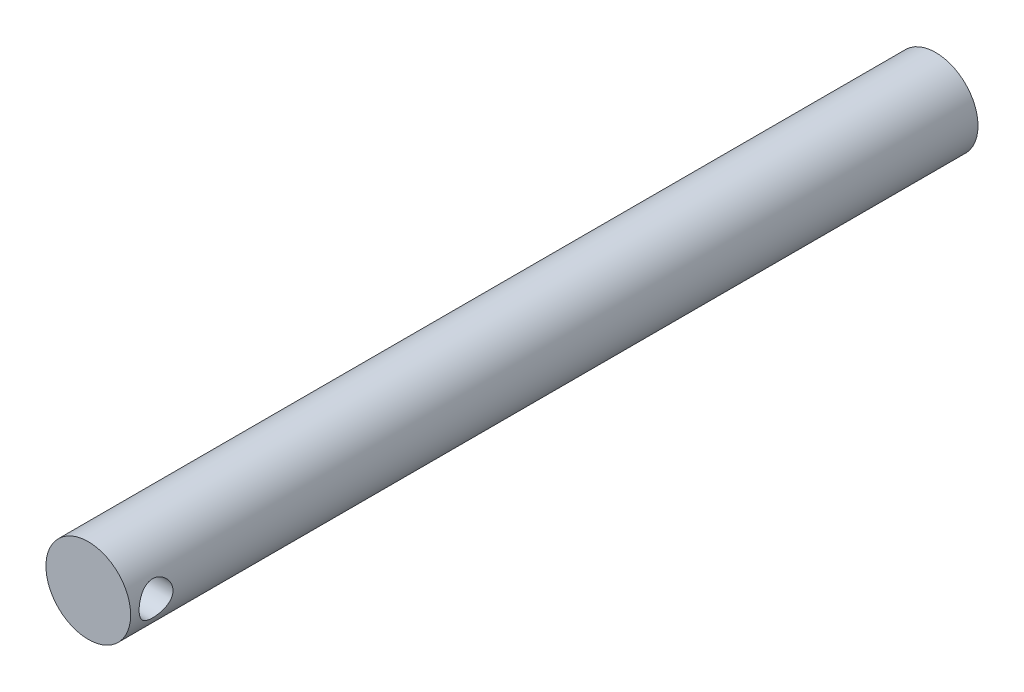
SolidWorks part; units mm, degrees
ref_plane "前视基准面" through (0, 0, 0) normal (0, 0, 1) x (1, 0, 0)
ref_plane "上视基准面" through (0, 0, 0) normal (0, 1, 0) x (1, 0, 0)
ref_plane "右视基准面" through (0, 0, 0) normal (1, 0, 0) x (0, 0, -1)
sketch "草图1" plane through (0, 0, 0) normal (0, 0, 1) x (1, 0, 0)
  circle A0 centre (0, 0) radius 2.5
  dimension "D1" = 5
extrude "凸台-拉伸1" add sketch "草图1" along normal blind 50
sketch "草图3" plane through (0, 0, 0) normal (1, 0, 0) x (0, 0, -1)
  line L0 (2.75, 0) -> (-2.75, 0) construction
  line L1 (-50, 2.5) -> (-50, -2.5) construction
  circle A0 centre (-48.5, 0) radius 1
  dimension "D1" = 2
  dimension "D2" = 1.5
extrude "切除-拉伸1" cut sketch "草图3" against normal through all both and the other way through all
